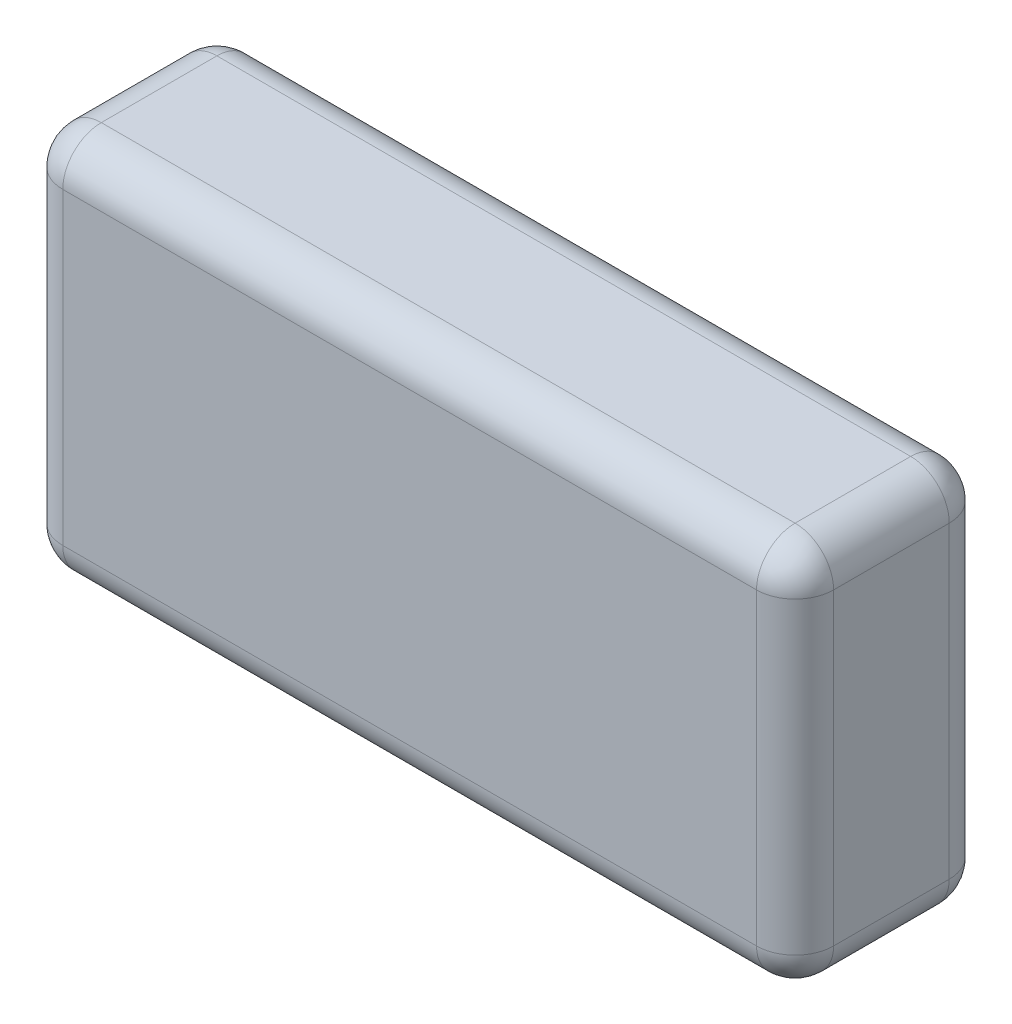
SolidWorks part; units mm, degrees
ref_plane "Plano frontal" through (0, 0, 0) normal (0, 0, 1) x (1, 0, 0)
ref_plane "Plano superior" through (0, 0, 0) normal (0, 1, 0) x (1, 0, 0)
ref_plane "Plano direito" through (0, 0, 0) normal (1, 0, 0) x (0, 0, -1)
sketch "Esboço1" plane through (0, 0, 0) normal (0, 1, 0) x (1, 0, 0)
  line L1 (-54.052, 23.4295) -> (145.948, 23.4295)
  line L2 (-54.052, 23.4295) -> (-54.052, -26.5705)
  line L3 (-54.052, -26.5705) -> (145.948, -26.5705)
  line L4 (145.948, 23.4295) -> (145.948, -26.5705)
extrude "Ressalto-extrusão1" add sketch "Esboço1" along normal blind 100
fillet "Filete9" radius 10 12 edges at (145.948, 100, 1.5705) (45.948, 100, 26.5705) (145.948, 50, 26.5705) (45.948, 0, 26.5705) (145.948, 0, 1.5705) (145.948, 50, -23.4295) (45.948, 100, -23.4295) (45.948, 0, -23.4295) (-54.052, 50, -23.4295) (-54.052, 100, 1.5705) (-54.052, 50, 26.5705) (-54.052, 0, 1.5705)
